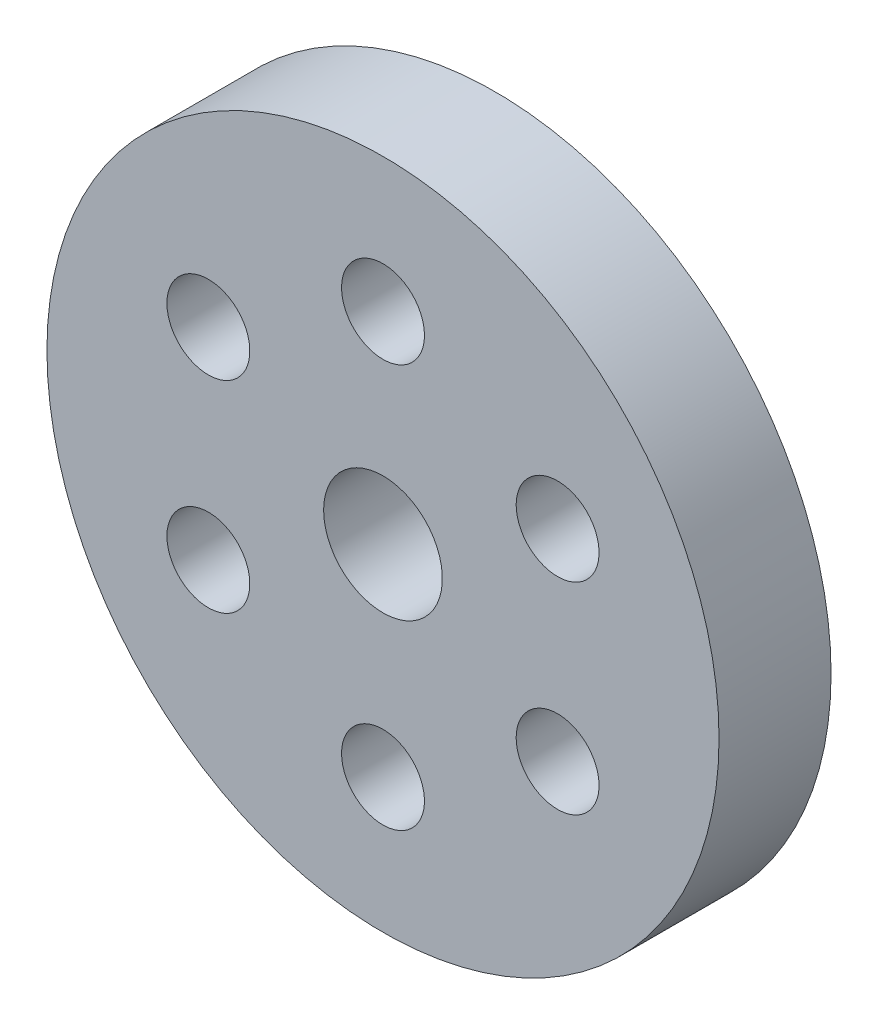
SolidWorks part; units mm, degrees
material "3.1325 (EN-AW 2017A)"
ref_plane "正面" through (0, 0, 0) normal (0, 0, 1) x (1, 0, 0)
ref_plane "平面" through (0, 0, 0) normal (0, 1, 0) x (1, 0, 0)
ref_plane "右側面" through (0, 0, 0) normal (1, 0, 0) x (0, 0, -1)
sketch "ｽｹｯﾁ1" plane through (0, 0, 0) normal (0, 0, 1) x (1, 0, 0)
  circle A1 centre (0, 0) radius 9 construction
  circle A2 centre (0, 0) radius 15
  point P5 (0, 9)
  point P20 (0, 0)
  dimension "D1" = 30
  dimension "D2" = 18
extrude "ﾎﾞｽ - 押し出し1" add sketch "ｽｹｯﾁ1" along normal blind 5 contours A2
hole_wizard "M5 すきま穴1" positions "3Dｽｹｯﾁ3" profile "ｽｹｯﾁ5" hole size "M5" standard "JIS" end condition through all
sketch3d "3Dｽｹｯﾁ3"
  point P0 (0, 0, 0)
sketch "ｽｹｯﾁ5" plane through (0, 0, 0) normal (1, 0, 0) x (0, 1, 0)
  line L0 (0, 0) -> (0, 5)
  line L1 (0, 5) -> (2.65, 5)
  line L2 (2.65, 5) -> (2.65, 0)
  line L5 (2.65, 0) -> (0, 0)
  line L11 (0, -6.35) -> (0, 107.95) construction
  dimension "通し穴の直径" = 5.3
  dimension "通し穴の深さ" = 5
hole_wizard "M3.5 すきま穴1" positions "3Dｽｹｯﾁ2" profile "ｽｹｯﾁ4" hole size "M3.5" standard "JIS" end condition through all
sketch3d "3Dｽｹｯﾁ2"
  point P31 (0, 9, 0)
sketch "ｽｹｯﾁ4" plane through (0, 9, 0) normal (1, 0, 0) x (0, 1, 0)
  line L0 (0, 0) -> (0, 5)
  line L1 (0, 5) -> (1.85, 5)
  line L2 (1.85, 5) -> (1.85, 0)
  line L5 (1.85, 0) -> (0, 0)
  line L11 (0, -6.35) -> (0, 107.95) construction
  dimension "通し穴の直径" = 3.7
  dimension "通し穴の深さ" = 5
pattern_circular "円形ﾊﾟﾀｰﾝ1" count 6 over 360 about axis through (0, 0, 0) along (0, 0, 1) of "M3.5 すきま穴1"
equation "\"フリッパ駆動ユニットプーリピン位置径\" = 18"
equation "\"D2@ｽｹｯﾁ1\"=\"フリッパ駆動ユニットプーリピン位置径\""
equation "\"フリッパ駆動ユニットプーリピン数\" = 6"
equation "\"D1@円形ﾊﾟﾀｰﾝ1\"=\"フリッパ駆動ユニットプーリピン数\""
